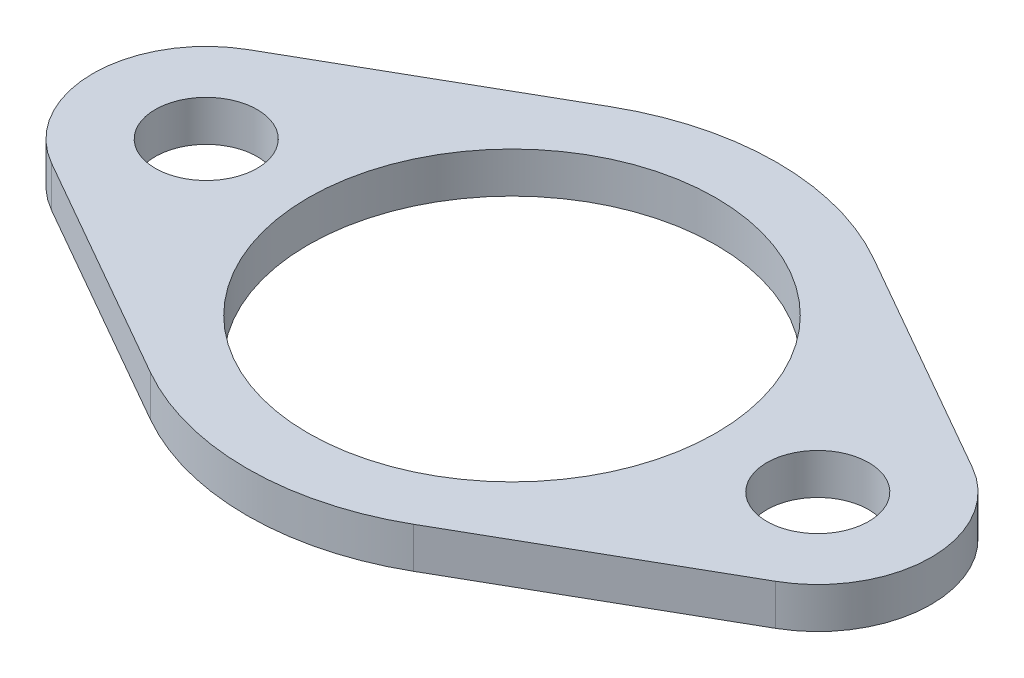
SolidWorks part; units mm, degrees
ref_plane "Front Plane" through (0, 0, 0) normal (0, 0, 1) x (1, 0, 0)
ref_plane "Top Plane" through (0, 0, 0) normal (0, 1, 0) x (1, 0, 0)
ref_plane "Right Plane" through (0, 0, 0) normal (1, 0, 0) x (0, 0, -1)
sketch "Sketch1" plane through (0, 0, 0) normal (0, 1, 0) x (1, 0, 0)
  line L0 (0, 0) -> (0, 6.5) construction
  line L1 (-8.8789, 2.4139) -> (-3.224, 5.6441)
  line L2 (3.224, 5.6441) -> (8.8789, 2.4139)
  line L3 (-7.5, 0) -> (7.5, 0) construction
  line L4 (-8.8789, -2.4139) -> (-3.224, -5.6441)
  line L5 (3.224, -5.6441) -> (8.8789, -2.4139)
  arc A1 (-8.8789, 2.4139) -> (-8.8789, -2.4139) centre (-7.5, 0) ccw
  arc A2 (8.8789, 2.4139) -> (8.8789, -2.4139) centre (7.5, 0) cw
  arc A3 (3.224, 5.6441) -> (-3.224, 5.6441) centre (0, 0) ccw
  arc A4 (-3.224, -5.6441) -> (3.224, -5.6441) centre (0, 0) ccw
  circle A5 centre (0, 0) radius 5
  circle A6 centre (-7.5, 0) radius 1.25
  circle A7 centre (7.5, 0) radius 1.25
  dimension "D1" = 10
  dimension "D2" = 5.56
  dimension "D4" = 2.5
  dimension "D3" = 7.5
extrude "Boss-Extrude1" add sketch "Sketch1" along normal blind 1
